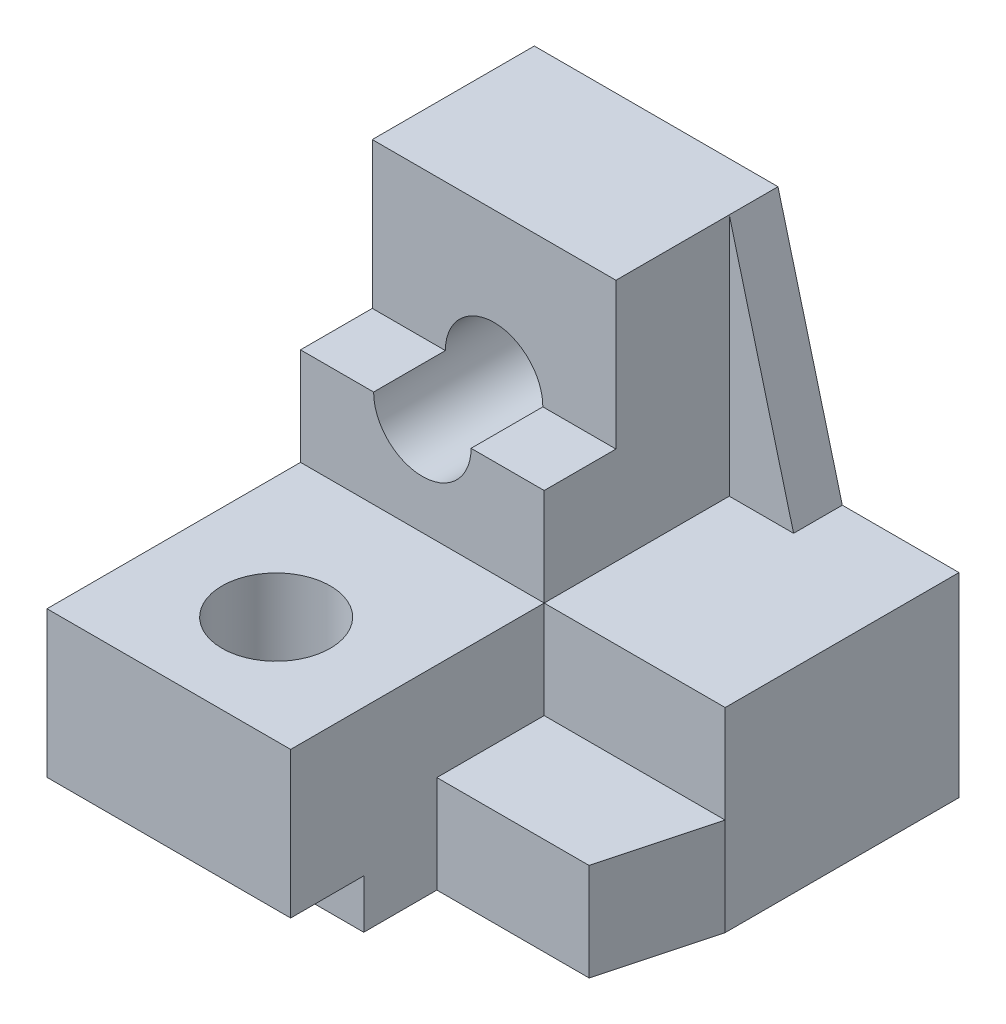
SolidWorks part; units mm, degrees
ref_plane "Alzado" through (0, 0, 0) normal (0, 0, 1) x (1, 0, 0)
ref_plane "Planta" through (0, 0, 0) normal (0, 1, 0) x (1, 0, 0)
ref_plane "Vista lateral" through (0, 0, 0) normal (1, 0, 0) x (0, 0, -1)
sketch "Croquis1" plane through (0, 0, 0) normal (0, 1, 0) x (1, 0, 0)
  line L1 (-50, 50) -> (50, 50)
  line L2 (-50, 50) -> (-50, -50)
  line L3 (-50, -50) -> (50, -50)
  line L4 (50, 50) -> (50, -50)
  line L5 (-50, 50) -> (50, -50) construction
  line L6 (-50, -50) -> (50, 50) construction
  point P0 (0, 0)
  dimension "D1" = 100
  dimension "100" = 100
extrude "Saliente-Extruir1" add sketch "Croquis1" along normal blind 20 contours L2 L1 L4 L3
sketch "Croquis2" plane through (0, 20, 0) normal (0, 1, 0) x (1, 0, 0)
  line L1 (-50, -50) -> (0, -50)
  line L2 (-50, -50) -> (-50, 2.0221)
  line L3 (-50, 2.0221) -> (0, 2.0221)
  line L4 (0, -50) -> (0, 2.0221)
extrude "Saliente-Extruir2" add sketch "Croquis2" along normal blind 20
sketch "Croquis6" plane through (0, 20, 0) normal (0, 1, 0) x (1, 0, 0)
  line L0 (0, 2.0221) -> (31.5969, 2.0221)
  line L1 (23.1498, -20) -> (50, 50)
  line L2 (23.1498, -20) -> (0, -20)
  line L3 (-50, 50) -> (50, 50) construction
  line L4 (0, -50) -> (0, 2.0221) construction
  line L5 (-50, -50) -> (0, -50) construction
  line L6 (0, -20) -> (0, -50)
  line L7 (0, -50) -> (50, -50)
  line L8 (50, -50) -> (50, -20)
  line L9 (50, 50) -> (50, -50) construction
  line L10 (50, -20) -> (0, -20)
  dimension "D1" = 70
  dimension "D2" = 100
extrude "Cortar-Extruir1" cut sketch "Croquis6" against normal blind 20 contours L3 L10 L2 L1
sketch "Croquis9" plane through (0, 0, 0) normal (1, 0, 0) x (0, 0, -1)
  line L0 (-50, 0) -> (-35, 0)
  line L1 (-20, 0) -> (-50, 0) construction
  line L2 (-35, 0) -> (-35, 10.032)
  line L3 (-35, 10.032) -> (-50, 10.032)
  line L4 (-50, 40) -> (-50, 0) construction
  line L5 (-50, 10.032) -> (-50, 0)
extrude "Cortar-Extruir8" cut sketch "Croquis9" against normal blind 50
sketch "Croquis10" plane through (0, 40, 0) normal (0, 1, 0) x (1, 0, 0)
  line L0 (0, 2.0221) -> (-50, 2.0221) construction
  line L1 (0, -50) -> (0, 2.0221) construction
  circle A0 centre (-25, -27.9779) radius 11.1076
  dimension "D1" = 30
  dimension "D2" = 25
extrude "Cortar-Extruir9" cut sketch "Croquis10" against normal blind 20
sketch "Croquis12" plane through (0, 20, 0) normal (0, 1, 0) x (1, 0, 0)
  line L0 (50, 50) -> (31.2436, -20)
  line L1 (50, -20) -> (0, -20) construction
  line L2 (-50, 50) -> (50, 50) construction
  line L3 (31.2436, -20) -> (50, -20)
  line L4 (50, -20) -> (50, 50)
  dimension "D1" = 75
extrude "Cortar-Extruir11" cut sketch "Croquis12" against normal blind 20
sketch "Croquis14" plane through (0, 20, 0) normal (0, 1, 0) x (1, 0, 0)
  line L0 (50, 50) -> (31.2436, -20) construction
  line L1 (-50, 50) -> (37.1444, 50)
  line L2 (-50, 50) -> (-50, 2.0221)
  line L3 (-50, 2.0221) -> (37.1444, 2.0221)
  line L4 (37.1444, 50) -> (37.1444, 2.0221)
extrude "Saliente-Extruir4" add sketch "Croquis14" along normal blind 20
sketch "Croquis15" plane through (0, 20, 0) normal (0, 1, 0) x (1, 0, 0)
  line L0 (37.1444, 50) -> (37.1444, 2.0221)
  line L1 (37.1444, 2.0221) -> (50, 50)
  line L2 (50, 50) -> (37.1444, 50)
extrude "Cortar-Extruir12" cut sketch "Croquis15" against normal blind 20
sketch "Croquis16" plane through (0, 40, 0) normal (0, 1, 0) x (1, 0, 0)
  line L0 (0, -50) -> (0, 2.0221) construction
  line L1 (-50, 50) -> (0, 50)
  line L2 (-50, 50) -> (-50, 2.0221)
  line L3 (-50, 2.0221) -> (0, 2.0221)
  line L4 (0, 50) -> (0, 2.0221)
  line L5 (0, -20) -> (0, 2.0221) construction
extrude "Saliente-Extruir5" add sketch "Croquis16" along normal blind 20
sketch "Croquis19" plane through (0, 0, -2.0221) normal (0, 0, 1) x (1, 0, 0)
  line L0 (-35, 60) -> (-15, 60)
  line L1 (-50, 60) -> (0, 60) construction
  arc A0 (-35, 60) -> (-15, 60) centre (-25, 60) ccw
extrude "Cortar-Extruir13" cut sketch "Croquis19" against normal through all
sketch "Croquis22" plane through (0, 60, 0) normal (0, 1, 0) x (1, 0, 0)
  line L0 (0, 2.0221) -> (0, 50) construction
  line L1 (-50, 50) -> (0, 50)
  line L2 (-50, 50) -> (-50, 16.7497)
  line L3 (-50, 16.7497) -> (0, 16.7497)
  line L4 (0, 50) -> (0, 16.7497)
extrude "Saliente-Extruir6" add sketch "Croquis22" along normal blind 20
sketch "Croquis23" plane through (0, 0, -16.7497) normal (0, 0, 1) x (1, 0, 0)
  line L0 (-35, 60) -> (-15, 60)
  line L1 (-50, 60) -> (-35, 60) construction
  line L2 (-50, 60) -> (-35, 60) construction
  arc A0 (-35, 60) -> (-15, 60) centre (-25, 60) cw
extrude "Cortar-Extruir14" cut sketch "Croquis23" against normal through all
sketch "Croquis25" plane through (0, 80, 0) normal (0, 1, 0) x (1, 0, 0)
  line L1 (-50, 50) -> (0, 50)
  line L2 (-50, 50) -> (-50, 16.7497)
  line L3 (-50, 16.7497) -> (0, 16.7497)
  line L4 (0, 50) -> (0, 16.7497)
extrude "Saliente-Extruir7" add sketch "Croquis25" along normal blind 10
sketch "Croquis29" plane through (0, 0, -50) normal (0, 0, -1) x (-1, 0, 0)
  line L0 (0, 90) -> (-13.2014, 40)
  line L1 (-37.1444, 40) -> (0, 40) construction
  line L2 (-13.2014, 40) -> (0, 40)
  line L3 (0, 40) -> (0.1413, 40.4455)
  line L4 (0.1413, 40.4455) -> (0, 90)
extrude "Saliente-Extruir10" add sketch "Croquis29" against normal blind 10
